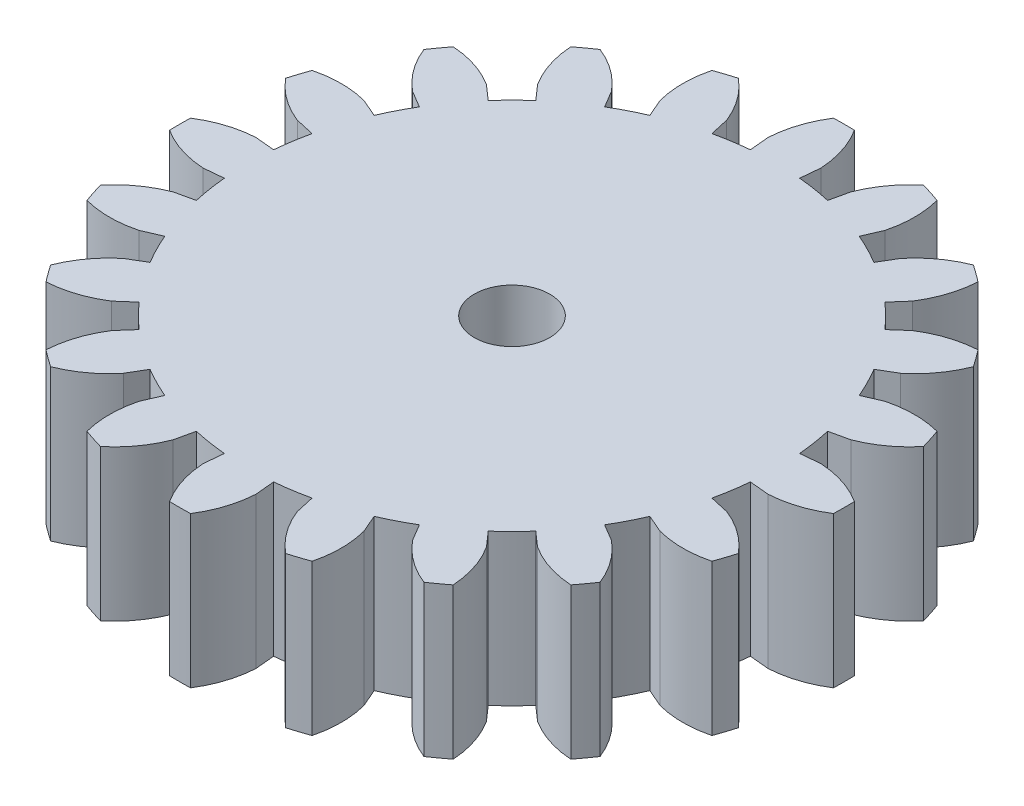
SolidWorks part; units mm, degrees
ref_plane "Спереди" through (0, 0, 0) normal (0, 0, 1) x (1, 0, 0)
ref_plane "Сверху" through (0, 0, 0) normal (0, 1, 0) x (1, 0, 0)
ref_plane "Справа" through (0, 0, 0) normal (1, 0, 0) x (0, 0, -1)
other "Configuration Table"
sketch "Эскиз1" plane through (0, 0, 0) normal (0, 1, 0) x (1, 0, 0)
  circle A0 centre (0, 0) radius 17.5
  dimension "D1" = 35
extrude "Бобышка-Вытянуть1" add sketch "Эскиз1" along normal blind 10
sketch "Эскиз2" plane through (0, 0, 0) normal (0, -1, 0) x (1, 0, 0)
  line L0 (0, 0) -> (0, 22) construction
  line L1 (0, 0) -> (-1.7523, 18.712) construction
  line L2 (0, 0) -> (1.7523, 18.712) construction
  line L5 (-1.5692, 19.9383) -> (0, 0) construction
  line L6 (0, 0) -> (1.5692, 19.9383) construction
  line L7 (-0.6949, 21.989) -> (0, 0) construction
  line L8 (-1.6317, 17.4238) -> (-1.7523, 18.712)
  line L9 (1.7523, 18.712) -> (1.6317, 17.4238)
  circle A0 centre (0, 0) radius 18.7938 construction
  circle A1 centre (0, 0) radius 20 construction
  circle A2 centre (0, 0) radius 22 construction
  arc A3 (-0.6949, 21.989) -> (0.6949, 21.989) centre (0, 0) cw
  arc A4 (-1.6317, 17.4238) -> (1.6317, 17.4238) centre (0, 0) cw
  circle A5 centre (0, 0) radius 17.5 construction
  arc A6 (-1.5692, 19.9383) -> (1.5692, 19.9383) centre (0, 0) cw construction
  arc A7 (-1.7523, 18.712) -> (-0.6949, 21.989) centre (5.0681, 18.3203) cw
  arc A8 (0.6949, 21.989) -> (1.7523, 18.712) centre (-5.0681, 18.3203) cw
  point P12 (0, 20)
  point P16 (0, 22)
  point P22 (0, 17.5)
  dimension "D1" = 37.5877
  dimension "D2" = 40
  dimension "D3" = 44
  dimension "D4" = 5.35
  dimension "D5" = 4.5
  dimension "D6" = 1.81
extrude "Бобышка-Вытянуть2" add sketch "Эскиз2" against normal blind 10
pattern_circular "Круговой массив1" count 20 over 360 about axis through (0, 0, 0) along (0, 1, 0) of "Бобышка-Вытянуть2"
sketch "Эскиз3" plane through (0, 0, 0) normal (0, -1, 0) x (1, 0, 0)
  circle A0 centre (0, 0) radius 2.5
  dimension "D1" = 5
extrude "Вырез-Вытянуть1" cut sketch "Эскиз3" against normal through all
equation "\"Ширина груза\"= 160"
equation "\"Глубина груза\"= 240"
equation "\"Высота груза\"= 160"
equation "\"Ширина ячейки\"= \"Ширина груза\" + 10"
equation "\"Глубина ячейки\"= \"Глубина груза\" + 10"
equation "\"Высота ячейки\"= \"Высота груза\" + 10 + 13"
equation "\"Колво ячеек ширина\"= 2"
equation "\"Колво ячеек высота\"= 2"
equation "\"Толщина стенки\" = \"Толщина тонких панелей\""
equation "\"Крепление дверцы\"= 5 "
equation "\"Ширина рейки\"= \"Толщина шестерни\""
equation "\"Высота рейки\"= 20"
equation "\"Высота пола\" = 2*\"Толщина тонких панелей\""
equation "\"Колво полозьев\"= 5"
equation "\"Отступ рейки\"= 20"
equation "\"Глубина каретки\"= \"Глубина ячейки\" + 30 + \"Мотор Y высота корпуса\" + 20 + \"Удлинение платформы по глубине\""
equation "\"Длинна рейки\" = (\"Ширина ячейки\"+\"Толщина вертикальных стенок\"+\"Крепление дверцы\")*\"Колво ячеек ширина\"+\"Ширина ячейки выгрузки\"*\"Колво выгрузки\"+\"Толщина вертикальных стенок\"+2*\"Отступ крепления мотора фиксации\"-\"Крепление дверцы\"*\"Колво ячеек ширина\""
equation "\"Отступ шпильки\"= 26"
equation "\"Диаметр шпильки\"= 5"
equation "\"Длинна шпильки\" = (\"Высота ячейки\"+\"Толщина горизонтальных плит\"+\"Высота пола\")*\"Колво ячеек высота\"+2*(\"Толщина горизонтальных плит\"+\"Отступ рейки\")"
equation "\"Ширина пластины\" = 50"
equation "\"Высота зона выгрузки\"= \"Высота ячейки\" * 2 + \"Толщина стенки\" * 2"
equation "\"Колво выгрузки\"= 1"
equation "\"Ширина ячейки выгрузки\" = \"Ширина ячейки\"+\"Толщина вертикальных стенок\"+2*\"Отступ крепления мотора фиксации\""
equation "\"Отступ крепления мотора фиксации\" = (70-\"Толщина вертикальных стенок\")/2"
equation "\"Мотор X ширина корпуса\"= 42.3"
equation "\"Мотор X высота корпуса\"= 42.3"
equation "\"Мотор X длина корпуса\"= 40"
equation "\"Мотор X вылет вала\"= 19.8"
equation "\"Мотор Y ширина корпуса\"= 42.3"
equation "\"Мотор Y высота корпуса\"= 42.3"
equation "\"Мотор Y длина корпуса\"= 48"
equation "\"Мотор Y вылет вала\"= 30"
equation "\"Мотор Z ширина корпуса\"= 42"
equation "\"Мотор Z высота корпуса\"= 42"
equation "\"Мотор Z длина корпуса\"= 40"
equation "\"Мотор Z вылет вала\"= 23"
equation "\"Мотор диаметр вала ПРЕДВ\"= 5"
equation "\"Мотор шаг крепления ПРЕДВ\"= 31"
equation "\"Мотор диаметр отверстий ПРЕДВ\"= 3"
equation "\"Мотор глубина отверстий ПРЕДВ\"= 4.5"
equation "\"Мотор диаметр буртика ПРЕДВ\"= 22"
equation "\"Мотор высота буртика ПРЕДВ\"= 2"
equation "\"Мотор диаметр шкива ПРЕДВ\"= 16"
equation "\"Мотор длина шкива ПРЕДВ\"= 12"
equation "\"Мотор отступ шкива ПРЕДВ\"= 5"
equation "\"Мотор X шаг градусов\"= 1.8"
equation "\"Мотор Y шаг градусов\"= 1.8"
equation "\"Мотор Z шаг градусов\"= 1.8"
equation "\"Мотор Y диаметр ротора\"= 25.78"
equation "\"Толщина шестерни\"= 10"
equation "\"D1@Бобышка-Вытянуть1\"=\"Толщина шестерни\""
equation "\"D1@Бобышка-Вытянуть2\"=\"Толщина шестерни\""
equation "\"D1@Эскиз3\"=\"Мотор диаметр вала ПРЕДВ\""
equation "\"Толщина тонких панелей\" = 6"
equation "\"Толщина вертикальных стенок\" = 6"
equation "\"Толщина горизонтальных плит\" = 6"
equation "\"Базовая высота корпуса\"= (\"Высота ячейки\"+\"Толщина тонких панелей\"+\"Высота пола\")*\"Колво ячеек высота\"+6*\"Толщина тонких панелей\"+\"Мотор X ширина корпуса\"+\"Мотор Y ширина корпуса\"+75"
equation "\"Высота корпуса\"= (\"Высота ячейки\"+\"Толщина горизонтальных плит\"+\"Высота пола\")*\"Колво ячеек высота\"+2*\"Толщина горизонтальных плит\"+4*\"Толщина тонких панелей\"+\"Мотор X ширина корпуса\"+\"Мотор Y ширина корпуса\"+75"
equation "\"Смещение центра корпуса\"= (\"Высота корпуса\"-\"Базовая высота корпуса\")/2-(\"Толщина горизонтальных плит\"-\"Толщина тонких панелей\")"
equation "\"Отметка пола\"= -\"Базовая высота корпуса\"/2+\"Толщина тонких панелей\""
equation "\"Отметка потолка\"= \"Отметка пола\"+\"Высота корпуса\"-2*\"Толщина горизонтальных плит\""
equation "\"Отметка верхней полки\"= \"Отметка потолка\"-(28+\"Толщина тонких панелей\")-\"Высота ячейки\"-\"Высота пола\""
equation "\"Отметка нижней полки\"= \"Отметка верхней полки\"-\"Высота ячейки\"-\"Высота пола\"-\"Толщина горизонтальных плит\""
